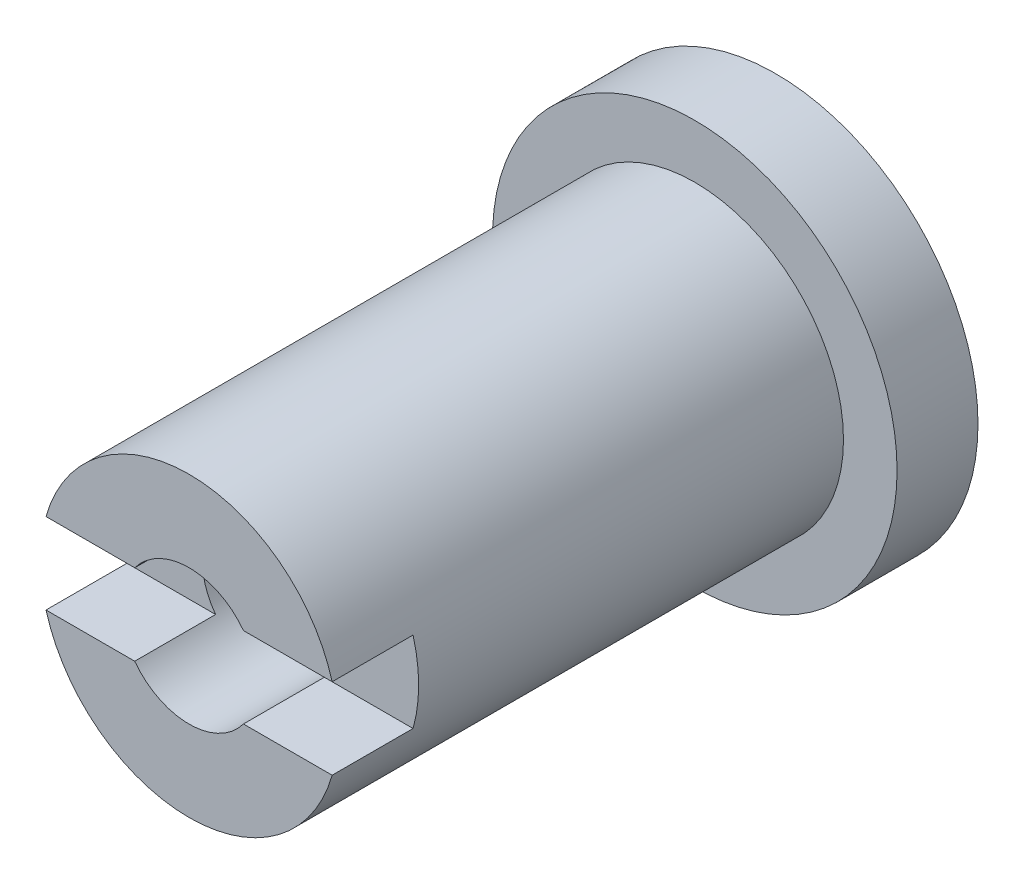
SolidWorks part; units mm, degrees
ref_plane "前视基准面" through (0, 0, 0) normal (0, 0, 1) x (1, 0, 0)
ref_plane "上视基准面" through (0, 0, 0) normal (0, 1, 0) x (1, 0, 0)
ref_plane "右视基准面" through (0, 0, 0) normal (1, 0, 0) x (0, 0, -1)
other "Configuration Table"
sketch "草图1" plane through (0, 0, 0) normal (0, 0, 1) x (1, 0, 0)
  circle A0 centre (0, 0) radius 10
  dimension "D1" = 20
extrude "拉伸-薄壁1" add sketch "草图1" along normal blind 4 thin thin type one direction reverse wall 6
sketch "草图2" plane through (0, 0, 4) normal (0, 0, 1) x (1, 0, 0)
  circle A0 centre (0, 0) radius 7.35
  dimension "D1" = 14.7
extrude "拉伸-薄壁2" add sketch "草图2" along normal blind 25 thin thin type one direction reverse wall 4
sketch "草图3" plane through (0, 0, 29) normal (0, 0, 1) x (1, 0, 0)
  line L1 (-7.8873, 2) -> (7.8873, 2)
  line L2 (-7.8873, 2) -> (-7.8873, -2)
  line L3 (-7.8873, -2) -> (7.8873, -2)
  line L4 (7.8873, 2) -> (7.8873, -2)
  line L5 (-7.8873, 2) -> (7.8873, -2) construction
  line L6 (-7.8873, -2) -> (7.8873, 2) construction
  point P0 (0, 0)
  dimension "D1" = 4
extrude "切除-拉伸1" cut sketch "草图3" against normal blind 4
